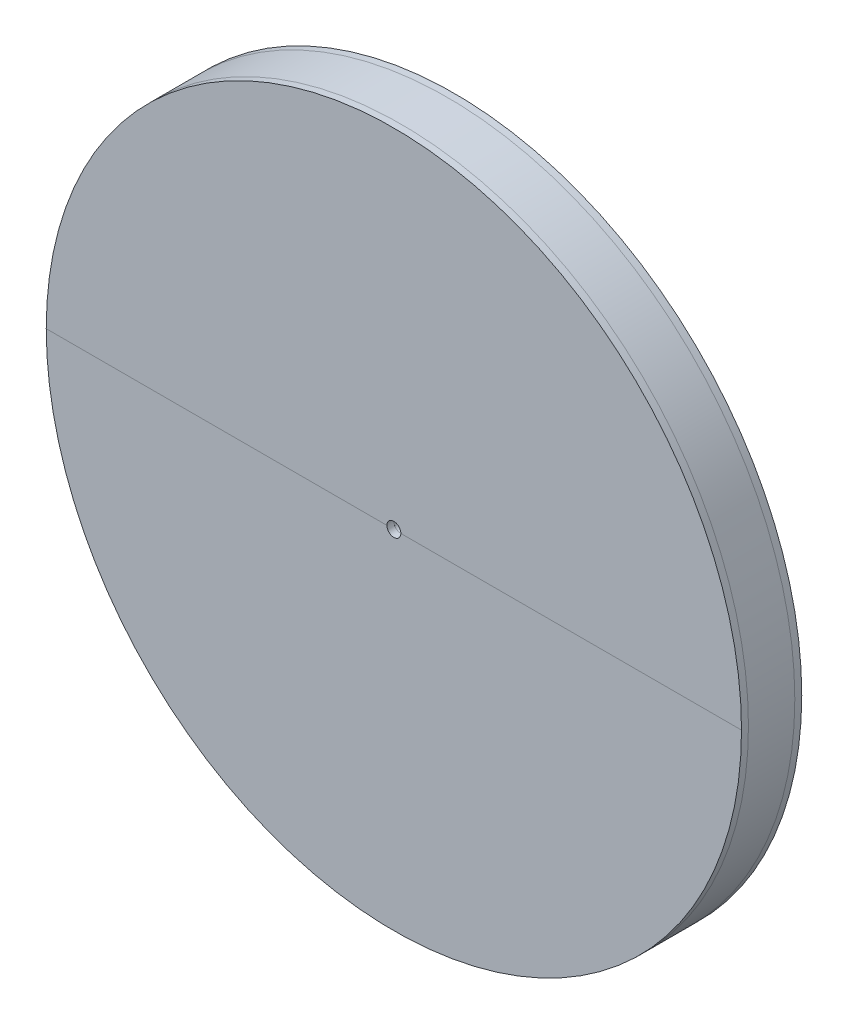
SolidWorks part; units mm, degrees
material "Pin"
ref_plane "Plan de face" through (0, 0, 0) normal (0, 0, 1) x (1, 0, 0)
ref_plane "Plan de dessus" through (0, 0, 0) normal (0, 1, 0) x (1, 0, 0)
ref_plane "Plan de droite" through (0, 0, 0) normal (1, 0, 0) x (0, 0, -1)
sketch "Esquisse1" plane through (0, 0, 0) normal (0, 0, 1) x (1, 0, 0)
  line L2 (-25, 137.7498) -> (-25, -137.7498)
  line L4 (-15, 139.1941) -> (-15, 20)
  line L5 (-15, 20) -> (15, 20)
  line L7 (-15, -20) -> (15, -20)
  line L9 (15, 139.1941) -> (15, 20)
  line L11 (25, 137.7498) -> (25, -137.7498)
  line L13 (-15, -20) -> (-15, -139.1941)
  line L14 (15, -20) -> (15, -139.1941)
  line L16 (0, 20) -> (0, -20) construction
  line L18 (-25, 0) -> (25, 0) construction
  circle A0 centre (0, 0) radius 150
  arc A1 (-25, 137.7498) -> (-25, -137.7498) centre (0, 0) ccw
  arc A2 (15, 139.1941) -> (-15, 139.1941) centre (0, 0) ccw
  arc A3 (25, -137.7498) -> (25, 137.7498) centre (0, 0) ccw
  arc A4 (-15, -139.1941) -> (15, -139.1941) centre (0, 0) ccw
  circle A5 centre (0, 0) radius 3
  dimension "D1" = 300
  dimension "D2" = 10
  dimension "D3" = 10
  dimension "D6" = 6
  dimension "D4" = 30
  dimension "D5" = 40
extrude "Boss.-Extru.1" add sketch "Esquisse1" along normal mid plane 20
sketch "Esquisse2" plane through (0, 0, -10) normal (0, 0, -1) x (-1, 0, 0)
  circle A0 centre (0, 0) radius 150 construction
  circle A1 centre (0, 0) radius 150
  circle A2 centre (0, 0) radius 3 construction
  circle A3 centre (0, 0) radius 3
extrude "Boss.-Extru.2" add sketch "Esquisse2" along normal blind 3 separate body
mirror "Symétrie1" about plane through (0, 0, 0) normal (0, 0, 1) of bodies 102
sketch "Esquisse4" plane through (0, 0, 13) normal (0, 0, 1) x (1, 0, 0)
  line L0 (-150, 0) -> (150, 0)
  circle A0 centre (0, 0) radius 150 construction
split line "Ligne de séparation1"
